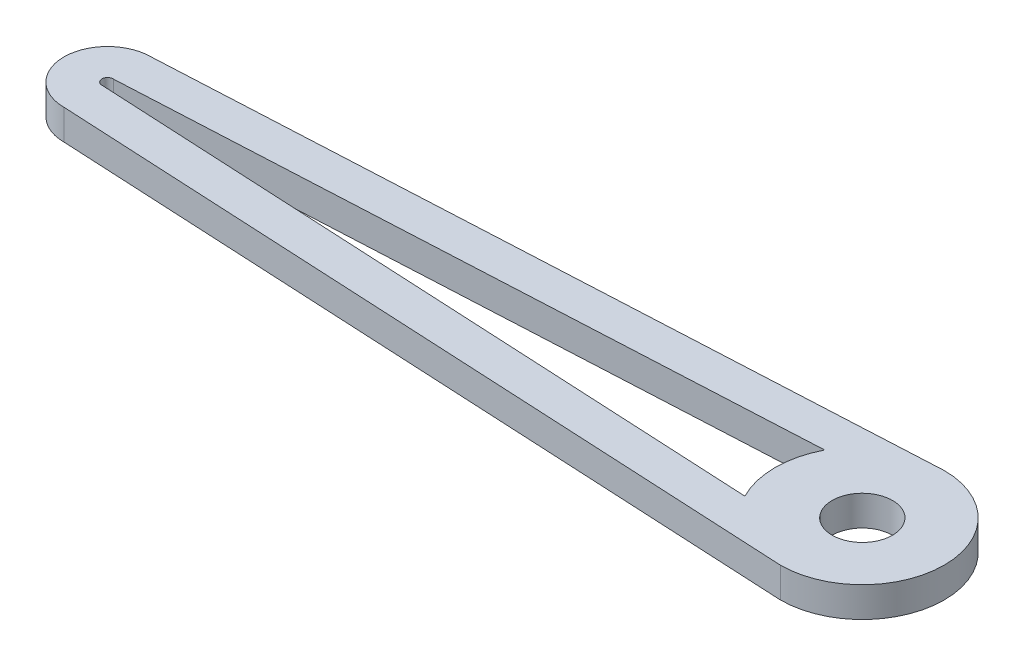
SolidWorks part; units mm, degrees
ref_plane "Front Plane" through (0, 0, 0) normal (0, 0, 1) x (1, 0, 0)
ref_plane "Top Plane" through (0, 0, 0) normal (0, 1, 0) x (1, 0, 0)
ref_plane "Right Plane" through (0, 0, 0) normal (1, 0, 0) x (0, 0, -1)
sketch "Sketch1" plane through (0, 0, 0) normal (0, 1, 0) x (1, 0, 0)
  line L0 (-21, 0) -> (21, 0) construction
  line L1 (-18.7072, 2.2928) -> (21, 4.311)
  line L2 (-18.7072, -2.2928) -> (21, -4.311)
  line L3 (-18.6805, 0.2916) -> (16.922, 2.1011)
  line L4 (-18.6805, -0.2916) -> (16.922, -2.1011)
  line L6 (-18.6805, 0.2916) -> (21.0429, 2.3106) construction
  line L7 (-18.6805, -0.2916) -> (21.0429, -2.3106) construction
  circle A0 centre (21, 0) radius 1.5875
  arc A1 (-18.7072, 2.2928) -> (-18.7072, -2.2928) centre (-18.7072, 0) ccw
  arc A2 (21, -4.311) -> (21, 4.311) centre (21, 0) ccw
  arc A4 (-18.6805, 0.2916) -> (-18.6805, -0.2916) centre (-18.7072, 0) ccw
  arc A5 (16.922, 2.1011) -> (16.922, -2.1011) centre (21, 0) ccw
  circle A7 centre (21, 0) radius 4.5875 construction
  arc A8 (21.0429, -2.3106) -> (21.0429, 2.3106) centre (21, 0) ccw construction
  point P3 (0, 0)
  point P18 (25.5875, 0)
  dimension "D2" = 3.175
  dimension "D1" = 42
  dimension "D3" = 2
  dimension "D4" = 3
extrude "Boss-Extrude1" add sketch "Sketch1" along normal mid plane 1.5875
